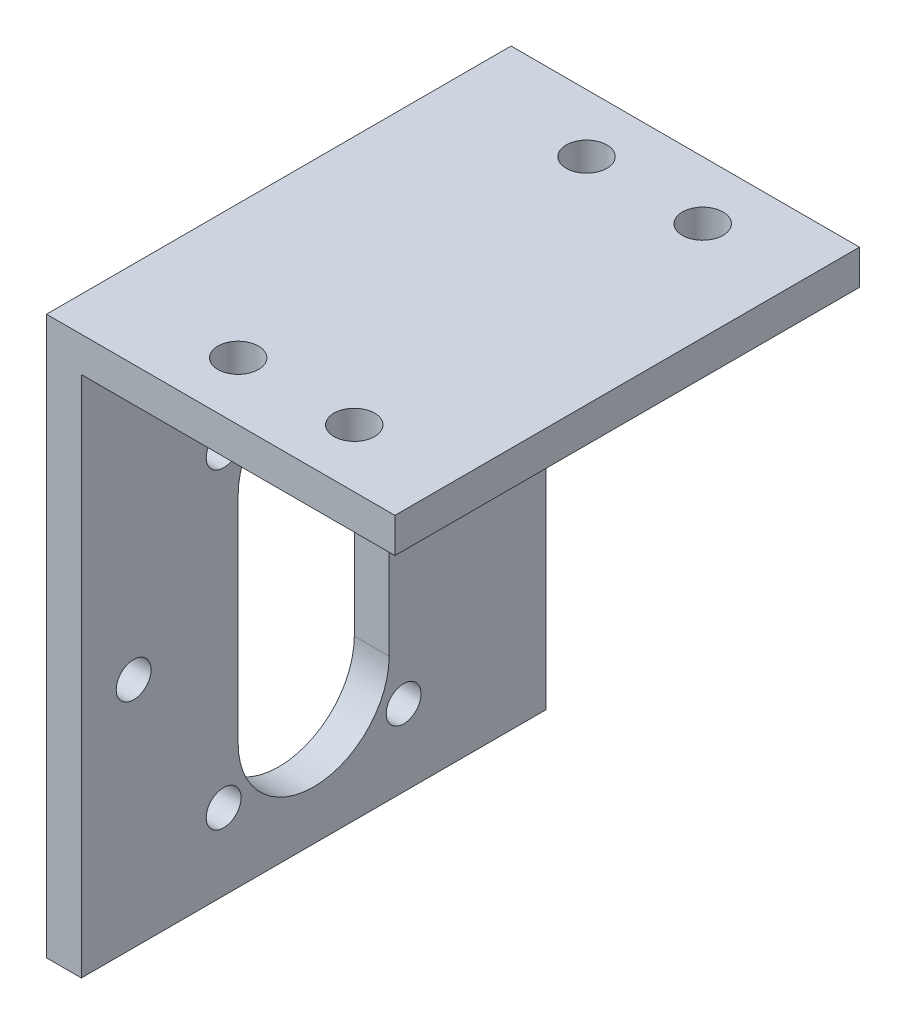
SolidWorks part; units mm, degrees
ref_plane "前视" through (0, 0, 0) normal (0, 0, 1) x (1, 0, 0)
ref_plane "上视" through (0, 0, 0) normal (0, 1, 0) x (1, 0, 0)
ref_plane "右视" through (0, 0, 0) normal (1, 0, 0) x (0, 0, -1)
sketch "草图1" plane through (0, 0, 0) normal (0, 1, 0) x (1, 0, 0)
  line L1 (0, 0) -> (30, 0)
  line L2 (0, 0) -> (0, -40)
  line L3 (0, -40) -> (30, -40)
  line L4 (30, 0) -> (30, -40)
  dimension "D1" = 40
  dimension "D2" = 30
extrude "凸台-拉伸1" add sketch "草图1" along normal blind 48
shell "抽壳1" thickness 3
sketch "草图2" plane through (0, 45, 0) normal (0, -1, 0) x (1, 0, 0)
  line L0 (3, 0) -> (3, 40) construction
  line L1 (3, 20) -> (26.0829, 20) construction
  circle A0 centre (11.5, 35) radius 1.75
  circle A1 centre (21.5, 35) radius 1.75
  circle A2 centre (21.5, 5) radius 1.75
  circle A3 centre (11.5, 5) radius 1.75
  dimension "D2" = 3.5
  dimension "D3" = 10
  dimension "D5" = 3.5
  dimension "D1" = 8.5
  dimension "D4" = 15
extrude "切除-拉伸1" cut sketch "草图2" against normal through all
sketch "草图3" plane through (0, 0, 0) normal (-1, 0, 0) x (0, 0, 1)
  line L1 (26.5, 20) -> (26.5, 29.2521)
  line L2 (13.5, 20) -> (13.5, 29.2521)
  line L4 (26.5, 20) -> (26.5, 10.7479)
  line L5 (13.5, 20) -> (13.5, 10.7479)
  circle A1 centre (27.75, 6.5766) radius 1.5
  circle A2 centre (12.25, 6.5766) radius 1.5
  circle A3 centre (4.5, 20) radius 1.5
  circle A4 centre (12.25, 33.4234) radius 1.5
  circle A5 centre (27.75, 33.4234) radius 1.5
  circle A6 centre (35.5, 20) radius 1.5
  arc A7 (26.5, 29.2521) -> (13.5, 29.2521) centre (20, 29.2521) ccw
  arc A8 (26.5, 10.7479) -> (13.5, 10.7479) centre (20, 10.7479) cw
  point P19 (20, 20)
  dimension "D3" = 3
  dimension "D4" = 6
extrude "切除-拉伸3" cut sketch "草图3" against normal through all
